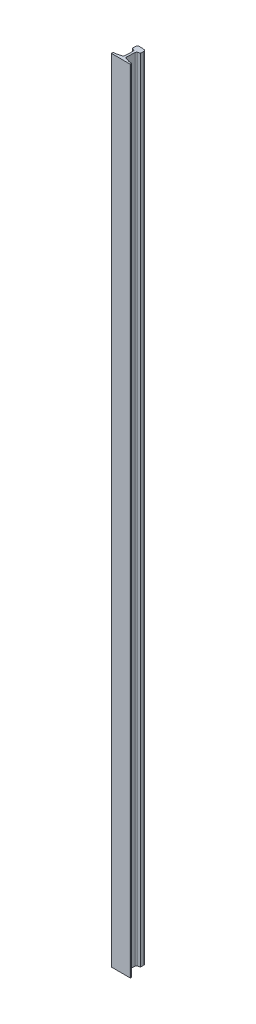
SolidWorks part; units mm, degrees
material "1023 Carbon Steel Sheet (SS)"
ref_plane "Front Plane" through (0, 0, 0) normal (0, 0, 1) x (1, 0, 0)
ref_plane "Top Plane" through (0, 0, 0) normal (0, 1, 0) x (1, 0, 0)
ref_plane "Right Plane" through (0, 0, 0) normal (1, 0, 0) x (0, 0, -1)
sketch "Sketch1" plane through (0, 0, 0) normal (0, 1, 0) x (1, 0, 0)
  line L0 (263.1667, 1014.5) -> (1315.8333, 1014.5) construction
  line L1 (0, 0) -> (0, 192.9833) construction
  line L2 (2.57, 0) -> (-70.43, 0)
  line L3 (-3.5794, 36.9461) -> (-0.5081, 98.6509)
  line L4 (-71.43, 1) -> (-71.43, 11.0149)
  line L5 (-68.7285, 14) -> (-44.7615, 16.3967)
  line L6 (2.57, 0) -> (10.3103, 154.8066) construction
  line L7 (-12.0274, 26.0784) -> (-40.8566, 17.186)
  line L8 (7.8627, 105.8678) -> (132.147, 99.6543) construction
  line L9 (9.6303, 141.2236) -> (9.6312, 141.2236) construction
  line L10 (-22.8308, 142.8465) -> (133.9146, 135.0102) construction
  line L11 (9.6303, 141.2236) -> (133.9146, 135.0102) construction
  line L12 (-8.1347, 110.4306) -> (-23.986, 116.6098)
  line L13 (-22.8308, 142.8465) -> (-25.2496, 118.6724)
  line L14 (-22.8308, 142.8465) -> (-26.0977, 77.5015) construction
  line L15 (-12.901, 157.1288) -> (-12.901, 97.1288) construction
  line L16 (-23.986, 116.6098) -> (5.9766, 115.1119) construction
  line L17 (18.041, 154.4007) -> (18.041, 94.4007) construction
  line L18 (42.0881, 139.6009) -> (40.3987, 113.2175) construction
  line L20 (42.0881, 139.6009) -> (42.0882, 115.363)
  line L21 (40.3987, 113.2175) -> (40.7771, 113.3229)
  line L22 (18.6856, 24.3546) -> (48.6856, 14.3546)
  line L23 (73.8685, 11) -> (52.6994, 13.4622)
  line L24 (76.57, 1) -> (76.57, 8.0149)
  line L25 (12.362, 35.6448) -> (15.472, 97.852)
  line L26 (2.57, 0) -> (75.57, 0)
  line L27 (122.5, 466) -> (612.5, 466) construction
  line L30 (73.8685, 11) -> (43.8725, 11.4889) construction
  line L31 (43.8725, 11.4889) -> (43.8725, 14.4889) construction
  line L32 (43.8725, 14.4889) -> (73.8685, 11) construction
  line L33 (-0.5081, 98.6509) -> (15.472, 97.852) construction
  line L35 (48.6856, 14.3546) -> (18.6856, 14.3546) construction
  line L36 (18.6856, 14.3546) -> (18.6856, 24.3546) construction
  line L40 (10.3094, 154.8067) -> (134.5936, 148.5932) construction
  line L41 (5.9766, 115.1119) -> (5.4773, 105.1244) construction
  line L42 (-29.8892, 1.6795) -> (-21.9605, 160.2534) construction
  line L44 (-23.986, 116.6098) -> (5.4773, 105.1244) construction
  line L45 (24.2366, 108.869) -> (40.6252, 113.4364)
  line L47 (40.7203, 112.2423) -> (42.0881, 139.6009) construction
  arc A0 (-71.43, 1) -> (-70.43, 0) centre (-70.43, 1) ccw
  arc A1 (-71.43, 11.0149) -> (-68.7285, 14) centre (-68.43, 11.0149) cw
  arc A2 (-40.8566, 17.186) -> (-44.7615, 16.3967) centre (-46.7516, 36.2974) cw
  arc A3 (-3.5794, 36.9461) -> (-12.0274, 26.0784) centre (-15.5644, 37.5453) cw
  arc A4 (-25.2496, 118.6724) -> (-23.986, 116.6098) centre (-23.2596, 118.4733) ccw
  arc A5 (-8.1347, 110.4306) -> (-0.5081, 98.6509) centre (-12.4931, 99.2501) cw
  arc A6 (30.8065, 152.7194) -> (42.0881, 139.6009) centre (29.0902, 139.8332) cw
  arc A7 (-10.2938, 154.7741) -> (-22.8308, 142.8465) centre (-9.8746, 141.7809) ccw
  arc A8 (30.8065, 152.7194) -> (-10.2938, 154.7741) centre (0.3231, -44.9439) ccw
  arc A9 (24.2366, 108.869) -> (15.472, 97.852) centre (27.4597, 97.31) ccw
  arc A10 (42.0882, 115.363) -> (40.6252, 113.4364) centre (40.0882, 115.363) cw
  arc A11 (76.57, 1) -> (75.57, 0) centre (75.57, 1) cw
  arc A14 (40.7203, 112.2423) -> (40.7771, 113.3229) centre (44.9556, 112.5616) cw
  arc A15 (12.362, 35.6448) -> (18.6856, 24.3546) centre (24.3412, 34.9383) ccw
  arc A16 (48.6856, 14.3546) -> (52.6994, 13.4622) centre (55.0101, 33.3283) ccw
  arc A17 (76.57, 8.0149) -> (73.8685, 11) centre (73.57, 8.0149) ccw
  point P2 (76.57, 11.9)
  point P15 (-71.43, 14)
  point P21 (2.57, 31.9262)
  point P52 (7.8627, 105.8678)
  point P53 (9.6275, 141.167)
  point P74 (76.57, 0)
  point P84 (10.3094, 154.8067)
  dimension "D7" = 3
  dimension "D11" = 12
  dimension "D16" = 2
  dimension "D17" = 12
  dimension "D24" = 3
  dimension "D25" = 20
  dimension "D20" = 13
  dimension "D31" = 13
  dimension "D15" = 2
  dimension "D4" = 20
  dimension "D5" = 1
  dimension "D6" = 1
  dimension "D12" = 60
  dimension "D26" = 30
  dimension "D27" = 10
  dimension "D32" = 30
  dimension "D33" = 10
  dimension "D8" = 148
  dimension "D10" = 74
  dimension "D9" = 2.862
  dimension "D13" = 65
  dimension "D14" = 155
  dimension "D21" = 11
  dimension "D22" = 14
  dimension "D18" = 49
  dimension "D19" = 13.6
extrude "Boss-Extrude1" add sketch "Sketch1" along normal blind 6160 contours L24 A17 L23 A16 L22 A15 L25 A9 L45 A10 L20 A6 A8 A7 L13 A4 L12 A5 L3 A3 L7 A2 L5 A1 L4 A0 L2 L26 A11
scale "Scale1" scale about centroid uniform scaling yes scale factor 0.5
equation "\"inc\"= atn ( 1 / 20deg )"
equation "\"D9@Sketch1\"= \"inc\""
